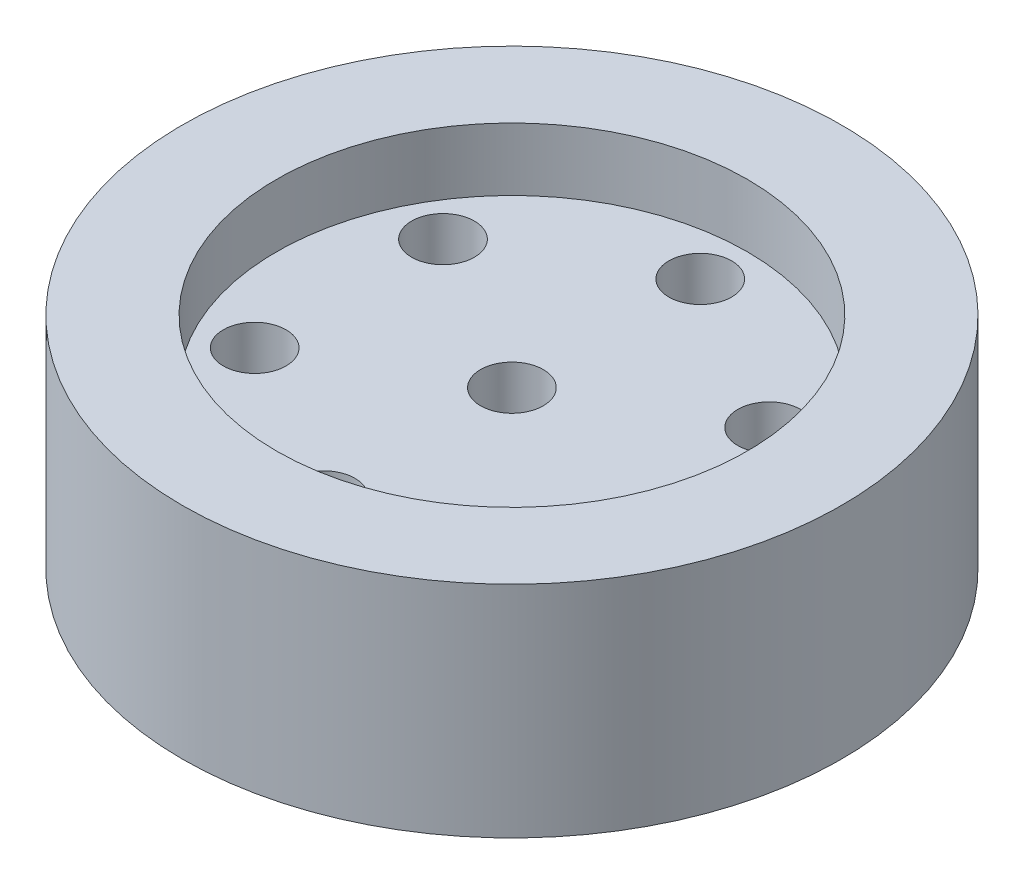
SolidWorks part; units mm, degrees
ref_plane "Front Plane" through (0, 0, 0) normal (0, 0, 1) x (1, 0, 0)
ref_plane "Top Plane" through (0, 0, 0) normal (0, 1, 0) x (1, 0, 0)
ref_plane "Right Plane" through (0, 0, 0) normal (1, 0, 0) x (0, 0, -1)
sketch "Sketch1" plane through (0, 0, 0) normal (0, 1, 0) x (1, 0, 0)
  circle A0 centre (0, 0) radius 21
  dimension "D1" = 42
extrude "Boss-Extrude1" add sketch "Sketch1" along normal mid plane 14
sketch "Sketch2" plane through (0, 7, 0) normal (0, 1, 0) x (1, 0, 0)
  circle A0 centre (0, 0) radius 15
  dimension "D1" = 30
extrude "Cut-Extrude1" cut sketch "Sketch2" against normal blind 4
sketch "Sketch3" plane through (0, -7, 0) normal (0, -1, 0) x (1, 0, 0)
  circle A0 centre (0, 0) radius 19
  circle A1 centre (0, 0) radius 5
  dimension "D1" = 38
  dimension "D2" = 10
extrude "Cut-Extrude2" cut sketch "Sketch3" against normal blind 4
sketch "Sketch4" plane through (0, -7, 0) normal (0, -1, 0) x (1, 0, 0)
  circle A0 centre (0, 0) radius 2
  dimension "D1" = 4
extrude "Cut-Extrude3" cut sketch "Sketch4" against normal through all
sketch "Sketch5" plane through (0, -3, 0) normal (0, -1, 0) x (1, 0, 0)
  circle A0 centre (0, 0) radius 12 construction
  circle A1 centre (0, 12) radius 2
  circle A2 centre (10.3923, 6) radius 2
  circle A3 centre (10.3923, -6) radius 2
  circle A4 centre (0, -12) radius 2
  circle A5 centre (-10.3923, -6) radius 2
  circle A6 centre (-10.3923, 6) radius 2
  point P18 (0, 0)
  dimension "D1" = 24
  dimension "D2" = 4
  dimension "D3" = 6
extrude "Cut-Extrude4" cut sketch "Sketch5" against normal through all
